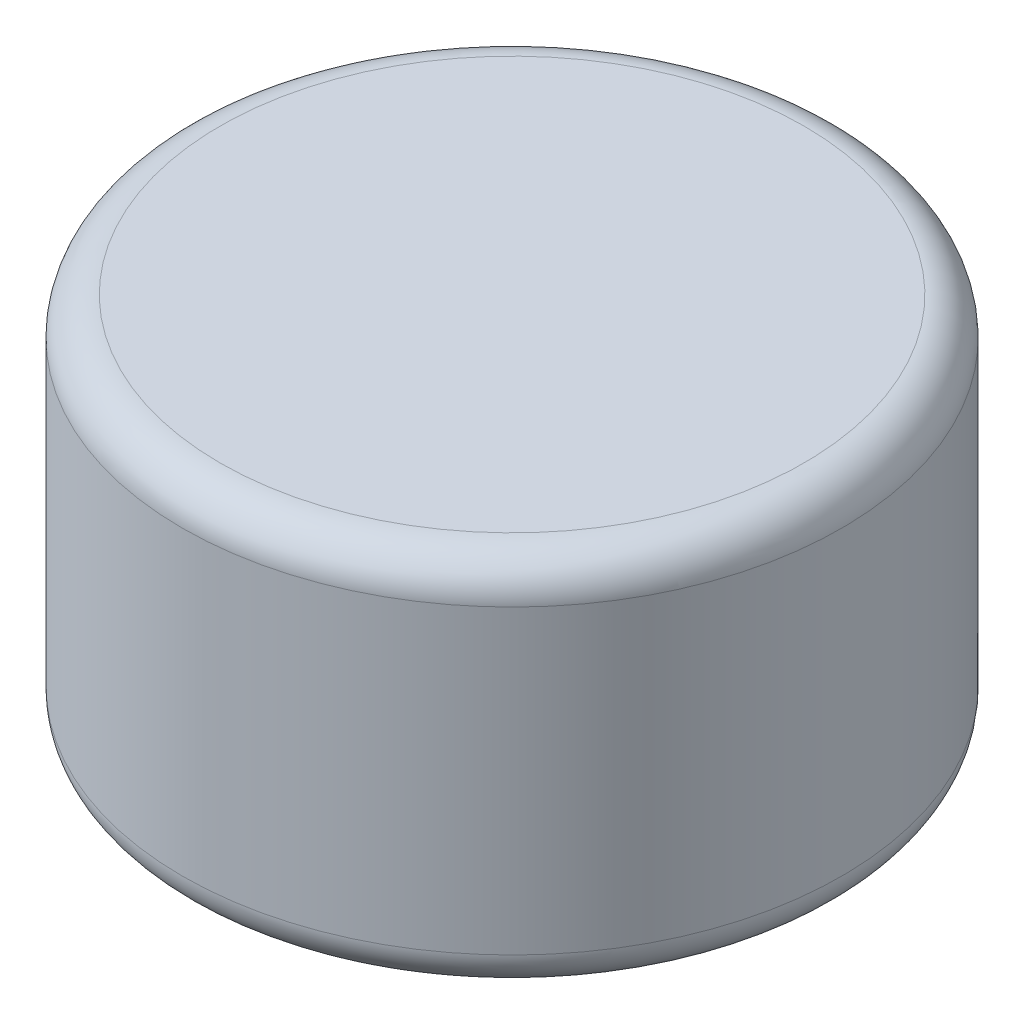
SolidWorks part; units mm, degrees
ref_plane "Front Plane" through (0, 0, 0) normal (0, 0, 1) x (1, 0, 0)
ref_plane "Top Plane" through (0, 0, 0) normal (0, 1, 0) x (1, 0, 0)
ref_plane "Right Plane" through (0, 0, 0) normal (1, 0, 0) x (0, 0, -1)
sketch "Sketch1" plane through (0, 0, 0) normal (0, 1, 0) x (1, 0, 0)
  circle A0 centre (0, 0) radius 5.5562
  dimension "OD" = 11.1125
extrude "Boss-Extrude1" add sketch "Sketch1" along normal mid plane 6.35
fillet "Fillet1" radius 0.635 2 edges at (0, -3.175, 5.5562) (0, 3.175, 5.5562)
equation "\"D1@Fillet1\"=\"Thickness@Boss-Extrude1\"/10"
